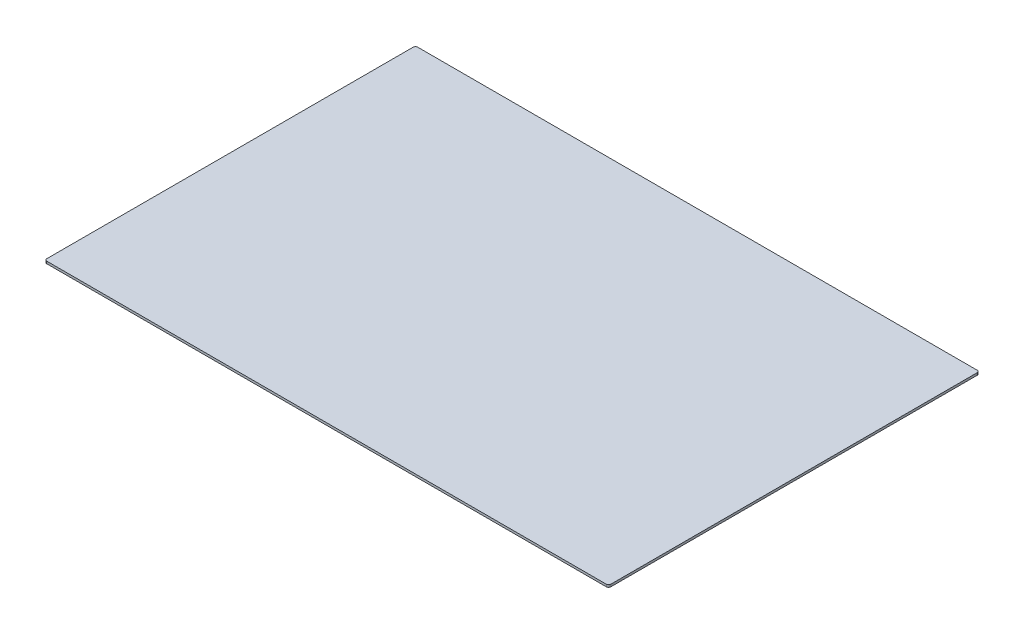
SolidWorks part; units mm, degrees
material "Silicon Rubber"
ref_plane "Front Plane" through (0, 0, 0) normal (0, 0, 1) x (1, 0, 0)
ref_plane "Top Plane" through (0, 0, 0) normal (0, 1, 0) x (1, 0, 0)
ref_plane "Right Plane" through (0, 0, 0) normal (1, 0, 0) x (0, 0, -1)
sketch "Sketch1" plane through (0, 0, 0) normal (0, 1, 0) x (1, 0, 0)
  line L1 (-61.75, 40.6) -> (61.75, 40.6)
  line L2 (-61.75, 40.6) -> (-61.75, -40.6)
  line L3 (-61.75, -40.6) -> (61.75, -40.6)
  line L4 (61.75, 40.6) -> (61.75, -40.6)
  line L5 (-61.75, 40.6) -> (61.75, -40.6) construction
  line L6 (-61.75, -40.6) -> (61.75, 40.6) construction
  point P0 (0, 0)
  dimension "D1" = 81.2
  dimension "D2" = 123.5
extrude "Boss-Extrude1" add sketch "Sketch1" along normal blind 0.5
fillet "Fillet1" radius 0.5 4 edges at (61.75, 0.25, 40.6) (61.75, 0.25, -40.6) (-61.75, 0.25, -40.6) (-61.75, 0.25, 40.6)
